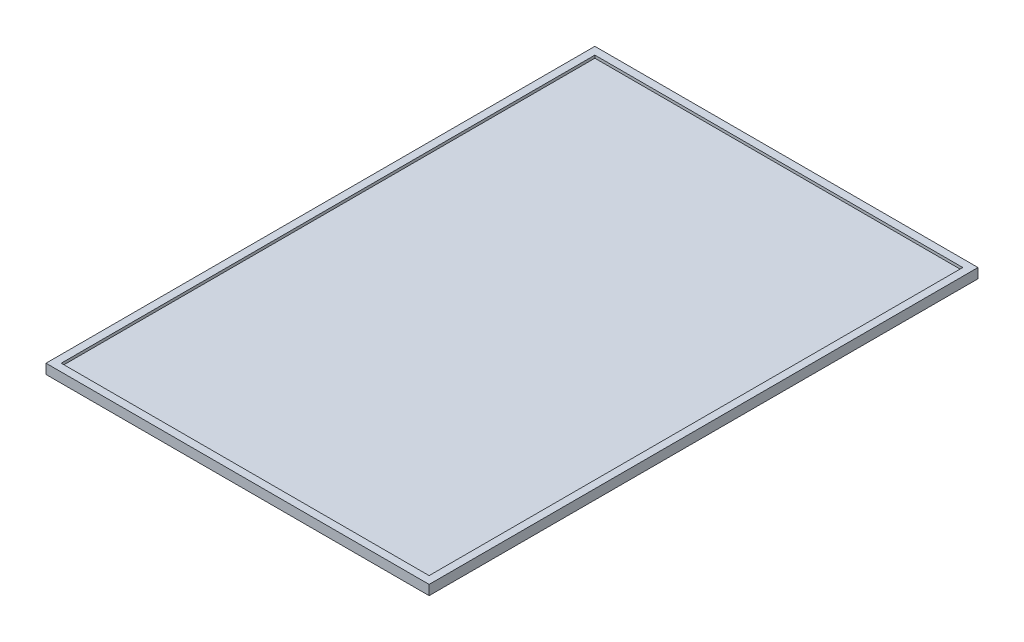
SolidWorks part; units mm, degrees
ref_plane "Front Plane" through (0, 0, 0) normal (0, 0, 1) x (1, 0, 0)
ref_plane "Top Plane" through (0, 0, 0) normal (0, 1, 0) x (1, 0, 0)
ref_plane "Right Plane" through (0, 0, 0) normal (1, 0, 0) x (0, 0, -1)
sketch "Sketch1" plane through (0, 0, 0) normal (0, 1, 0) x (1, 0, 0)
  line L1 (-352.5, -505) -> (352.5, -505)
  line L2 (-352.5, -505) -> (-352.5, 505)
  line L3 (-352.5, 505) -> (352.5, 505)
  line L4 (352.5, -505) -> (352.5, 505)
  line L5 (-352.5, -505) -> (352.5, 505) construction
  line L6 (-352.5, 505) -> (352.5, -505) construction
  point P0 (0, 0)
  dimension "D1" = 705
  dimension "D2" = 1010
extrude "Boss-Extrude1" add sketch "Sketch1" along normal blind 18
sketch "Sketch2" plane through (0, 18, 0) normal (0, 1, 0) x (1, 0, 0)
  line L0 (338.5, 491) -> (338.5, 505) construction
  line L1 (-338.5, -491) -> (338.5, -491)
  line L2 (-338.5, -491) -> (-338.5, 491)
  line L3 (-338.5, 491) -> (338.5, 491)
  line L4 (338.5, -491) -> (338.5, 491)
  line L5 (-338.5, -491) -> (338.5, 491) construction
  line L6 (-338.5, 491) -> (338.5, -491) construction
  line L7 (352.5, 505) -> (-352.5, 505) construction
  line L8 (-338.5, -491) -> (-338.5, -505) construction
  line L9 (352.5, -505) -> (352.5, 505) construction
  line L10 (352.5, 491) -> (338.5, 491) construction
  line L11 (-352.5, -505) -> (352.5, -505) construction
  line L13 (-352.5, 505) -> (-352.5, -505) construction
  line L14 (-352.5, -491) -> (-338.5, -491) construction
  point P0 (0, 0)
  dimension "D1" = 14
extrude "Cut-Extrude1" cut sketch "Sketch2" against normal blind 5
sketch "Sketch3" plane through (0, 13, 0) normal (0, 1, 0) x (1, 0, 0)
  line L0 (-352.5, 203.516) -> (352.5, 203.516)
  line L1 (352.5, 203.516) -> (0, -407.0319)
  line L2 (0, -407.0319) -> (-352.5, 203.516)
  line L3 (-352.5, 505) -> (-352.5, -505) construction
  line L4 (352.5, -505) -> (352.5, 505) construction
  circle A0 centre (0, 0) radius 407.0319
  dimension "D1" = 60
  dimension "D2" = 60
sketch "Sketch4" plane through (0, 0, 0) normal (0, -1, 0) x (1, 0, 0)
  line L8 (338, -490.5) -> (338, 490.5)
  line L9 (338, 490.5) -> (-338, 490.5)
  line L10 (-338, 490.5) -> (-338, -490.5)
  line L11 (-338, -490.5) -> (338, -490.5)
  line L12 (338, -490.5) -> (338, 490.5)
  line L13 (338, 490.5) -> (-338, 490.5)
  line L14 (-338, 490.5) -> (-338, -490.5)
  line L15 (-338, -490.5) -> (338, -490.5)
  dimension "D1" = 14.5
extrude "Cut-Extrude2" cut sketch "Sketch4" against normal blind 6
